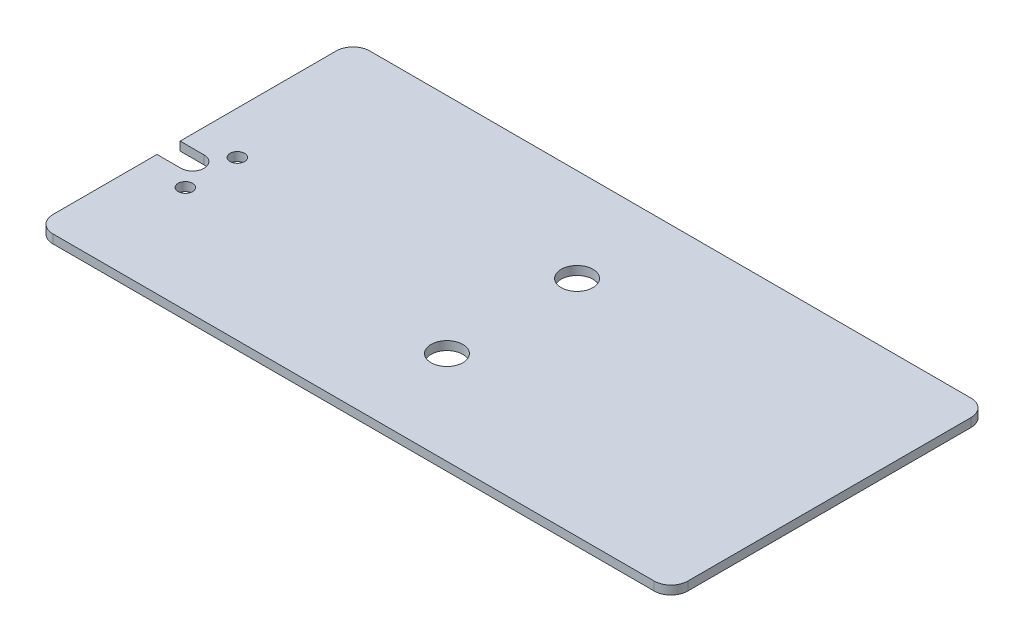
SolidWorks part; units mm, degrees
ref_plane "Спереди" through (0, 0, 0) normal (0, 0, 1) x (1, 0, 0)
ref_plane "Сверху" through (0, 0, 0) normal (0, 1, 0) x (1, 0, 0)
ref_plane "Справа" through (0, 0, 0) normal (1, 0, 0) x (0, 0, -1)
other "Configuration Table"
sketch "Эскиз1" plane through (0, 0, 0) normal (0, 1, 0) x (1, 0, 0)
  line L1 (-110, -55) -> (110, -55)
  line L2 (-110, -55) -> (-110, 55)
  line L3 (-110, 55) -> (110, 55)
  line L4 (110, -55) -> (110, 55)
  line L5 (-110, -55) -> (110, 55) construction
  line L6 (-110, 55) -> (110, -55) construction
  point P0 (0, 0)
  dimension "D1" = 220
  dimension "D2" = 110
extrude "Бобышка-Вытянуть1" add sketch "Эскиз1" along normal blind 3
sketch "Эскиз2" plane through (0, 0, 0) normal (0, -1, 0) x (1, 0, 0)
  line L0 (-110, -49) -> (-110, 49) construction
  line L1 (-110, -49) -> (-110, 49)
  line L2 (109.8, -49) -> (109.8, 49)
  line L3 (104, 54.8) -> (-104, 54.8)
  line L4 (-109.8, 49) -> (-109.8, -49)
  line L5 (-104, -54.8) -> (104, -54.8)
  line L6 (110, -49) -> (110, 49)
  line L7 (104, 55) -> (-104, 55)
  line L8 (-110, 49) -> (-110, -49)
  line L9 (-104, -55) -> (104, -55)
  line L10 (110, -49) -> (110, 49)
  line L11 (104, 55) -> (-104, 55)
  line L12 (-110, 49) -> (-110, -49)
  line L13 (-104, -55) -> (104, -55)
  line L14 (110, -55) -> (110, 55)
  line L15 (-110, -55) -> (110, -55)
  line L16 (-110, 55) -> (-110, -55)
  line L17 (110, 55) -> (-110, 55)
  line L18 (110, -55) -> (110, 55)
  line L19 (-110, -55) -> (110, -55)
  line L20 (-110, 55) -> (-110, -55)
  line L21 (110, 55) -> (-110, 55)
  arc A0 (109.8, 49) -> (104, 54.8) centre (104, 49) ccw
  arc A1 (-104, 54.8) -> (-109.8, 49) centre (-104, 49) ccw
  arc A2 (-109.8, -49) -> (-104, -54.8) centre (-104, -49) ccw
  arc A3 (104, -54.8) -> (109.8, -49) centre (104, -49) ccw
  arc A4 (110, 49) -> (104, 55) centre (104, 49) ccw
  arc A5 (-104, 55) -> (-110, 49) centre (-104, 49) ccw
  arc A6 (-110, -49) -> (-104, -55) centre (-104, -49) ccw
  arc A7 (104, -55) -> (110, -49) centre (104, -49) ccw
  arc A8 (110, 49) -> (104, 55) centre (104, 49) ccw construction
  arc A9 (-104, 55) -> (-110, 49) centre (-104, 49) ccw construction
  arc A10 (-110, -49) -> (-104, -55) centre (-104, -49) ccw construction
  arc A11 (104, -55) -> (110, -49) centre (104, -49) ccw construction
  line M13 (110, -55) -> (110, 55)
  line M14 (110, 55) -> (-110, 55)
  line M15 (-110, 55) -> (-110, -55)
  line M16 (-110, -55) -> (110, -55)
  dimension "D1" = 0
  dimension "D2" = 0
  dimension "D3" = 0.2
extrude "Вырез-Вытянуть1" cut sketch "Эскиз2" against normal blind 10 contours A3 L5 A2 L4 A1 L3 A0 L2 M16 M13 M14 M15
sketch "Эскиз3" plane through (0, 3, 0) normal (0, 1, 0) x (1, 0, 0)
  line L0 (-95, -18) -> (-95, 0) construction
  line L1 (-1095, -9) -> (48905, -9) construction
  line L2 (-101.5, -5) -> (-109.8, -5)
  line L3 (-101.5, -13) -> (-109.8, -13)
  line L4 (104, 54.8) -> (-104, 54.8)
  line L5 (-109.8, 49) -> (-109.8, -49)
  line L6 (-104, -54.8) -> (104, -54.8)
  line L7 (109.8, -49) -> (109.8, 49)
  line L8 (104, 54.8) -> (-104, 54.8)
  line L9 (-109.8, 49) -> (-109.8, -49)
  line L10 (-104, -54.8) -> (104, -54.8)
  line L11 (109.8, -49) -> (109.8, 49)
  line L12 (-97.5, 0) -> (-97.5, -18) construction
  circle A0 centre (-95, -18) radius 1.5875 construction
  circle A1 centre (-95, -18) radius 1.5875
  circle A2 centre (-95, 0) radius 1.5875 construction
  circle A3 centre (-95, 0) radius 1.5875
  arc A4 (109.8, 49) -> (104, 54.8) centre (104, 49) ccw
  arc A5 (-104, 54.8) -> (-109.8, 49) centre (-104, 49) ccw
  arc A6 (-109.8, -49) -> (-104, -54.8) centre (-104, -49) ccw
  arc A7 (104, -54.8) -> (109.8, -49) centre (104, -49) ccw
  arc A8 (109.8, 49) -> (104, 54.8) centre (104, 49) ccw
  arc A9 (-104, 54.8) -> (-109.8, 49) centre (-104, 49) ccw
  arc A10 (-109.8, -49) -> (-104, -54.8) centre (-104, -49) ccw
  arc A11 (104, -54.8) -> (109.8, -49) centre (104, -49) ccw
  circle A12 centre (-95, 0) radius 2.5
  circle A13 centre (-95, -18) radius 2.5
  arc A14 (-101.5, -13) -> (-101.5, -5) centre (-101.5, -9) ccw
  arc A15 (-101.5, -5) -> (-105.5, -9) centre (-101.5, -9) ccw construction
  arc A16 (-105.5, -9) -> (-101.5, -13) centre (-101.5, -9) ccw construction
  point P23 (-95, -9)
  line M13 (-109.8, 49) -> (-109.8, -49)
  dimension "D2" = 8
  dimension "D3" = 5
  dimension "D1" = 0
extrude "Вырез-Вытянуть2" cut sketch "Эскиз3" against normal through all contours A12 A3 | A3 | A13 A1 | A1 | L3 A14 L2 M13
sketch "Эскиз4" plane through (0, 3, 0) normal (0, 1, 0) x (1, 0, 0)
  circle A1 centre (0, 22.5) radius 5.5
  circle A2 centre (0, 22.5) radius 5.5
  circle A3 centre (0, -22.5) radius 5.5
  circle A4 centre (0, -22.5) radius 5.5
  dimension "D1" = 0
  dimension "D2" = 0
extrude "Вырез-Вытянуть3" cut sketch "Эскиз4" against normal through all contours A2 | A4
